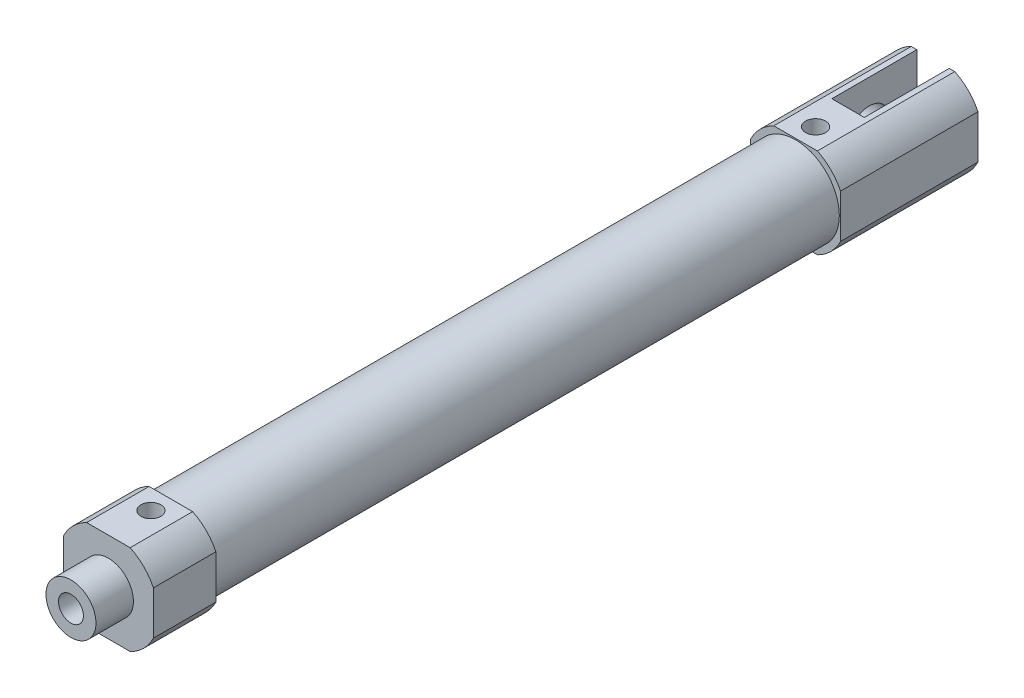
SolidWorks part; units mm, degrees
ref_plane "Front Plane" through (0, 0, 0) normal (0, 0, 1) x (1, 0, 0)
ref_plane "Top Plane" through (0, 0, 0) normal (0, 1, 0) x (1, 0, 0)
ref_plane "Right Plane" through (0, 0, 0) normal (1, 0, 0) x (0, 0, -1)
sketch "Sketch1" plane through (0, 0, 0) normal (0, 0, 1) x (1, 0, 0)
  line L1 (-4.3589, -9) -> (4.3589, -9)
  line L2 (-9, -4.3589) -> (-9, 4.3589)
  line L3 (-4.3589, 9) -> (4.3589, 9)
  line L4 (9, -4.3589) -> (9, 4.3589)
  line L5 (-7.0711, -7.0711) -> (7.0711, 7.0711) construction
  line L6 (-7.0711, 7.0711) -> (7.0711, -7.0711) construction
  circle A0 centre (0, 0) radius 10
  dimension "D1" = 20
extrude "Boss-Extrude1" add sketch "Sketch1" along normal blind 12.5 contours L4 A0 L3 L2 L1
sketch "Sketch2" plane through (0, 0, 12.5) normal (0, 0, 1) x (1, 0, 0)
  circle A0 centre (0, 0) radius 5
extrude "Boss-Extrude2" add sketch "Sketch2" along normal blind 7.5
sketch "Sketch3" plane through (0, 0, 0) normal (0, 0, -1) x (-1, 0, 0)
  circle A0 centre (0, 0) radius 8.75
extrude "Boss-Extrude3" add sketch "Sketch3" along normal blind 125
sketch "Sketch6" plane through (0, 0, -125) normal (0, 0, -1) x (-1, 0, 0)
  line L1 (-4.3589, -9) -> (4.3589, -9)
  line L2 (-9, -4.3589) -> (-9, 4.3589)
  line L3 (-4.3589, 9) -> (4.3589, 9)
  line L4 (9, -4.3589) -> (9, 4.3589)
  line L5 (-7.0711, -7.0711) -> (7.0711, 7.0711) construction
  line L6 (-7.0711, 7.0711) -> (7.0711, -7.0711) construction
  arc A0 (9, 4.3589) -> (4.3589, 9) centre (0, 0) ccw
  arc A1 (4.3589, -9) -> (9, -4.3589) centre (0, 0) ccw
  arc A2 (-9, -4.3589) -> (-4.3589, -9) centre (0, 0) ccw
  arc A3 (-4.3589, 9) -> (-9, 4.3589) centre (0, 0) ccw
extrude "Boss-Extrude4" add sketch "Sketch6" along normal blind 27.5
sketch "Sketch7" plane through (0, 0, -152.5) normal (0, 0, -1) x (-1, 0, 0)
  line L0 (4.3589, 9) -> (-4.3589, 9) construction
  line L1 (-3.25, -9) -> (3.25, -9)
  line L2 (-3.25, -9) -> (-3.25, 9)
  line L3 (-3.25, 9) -> (3.25, 9)
  line L4 (3.25, -9) -> (3.25, 9)
  line L5 (-3.25, -9) -> (3.25, 9) construction
  line L6 (-3.25, 9) -> (3.25, -9) construction
  point P0 (0, 0)
  dimension "D1" = 6.5
extrude "Cut-Extrude1" cut sketch "Sketch7" against normal blind 17
sketch "Sketch8" plane through (-9, 0, 0) normal (-1, 0, 0) x (0, 0, 1)
  line L0 (-152.5, -4.3589) -> (-152.5, 4.3589) construction
  circle A0 centre (-143, 0) radius 4
  point P2 (-152.5, 0)
  dimension "D1" = 9.5
extrude "Cut-Extrude2" cut sketch "Sketch8" against normal blind 17
sketch "Sketch9" plane through (0, 9, 0) normal (0, 1, 0) x (1, 0, 0)
  line L0 (-4.3589, 125) -> (4.3589, 125) construction
  circle A0 centre (0, 129) radius 2
  point P2 (0, 125)
  dimension "D1" = 4
extrude "Cut-Extrude3" cut sketch "Sketch9" against normal blind 4
sketch "Sketch10" plane through (0, 9, 0) normal (0, 1, 0) x (1, 0, 0)
  line L0 (-4.3589, 0) -> (4.3589, 0) construction
  circle A0 centre (0, -4) radius 2
  point P2 (0, 0)
  dimension "D1" = 4
extrude "Cut-Extrude4" cut sketch "Sketch10" against normal blind 4
sketch "Sketch11" plane through (0, 0, 20) normal (0, 0, 1) x (1, 0, 0)
  circle A0 centre (0, 0) radius 2.5
extrude "Cut-Extrude5" cut sketch "Sketch11" against normal blind 100
